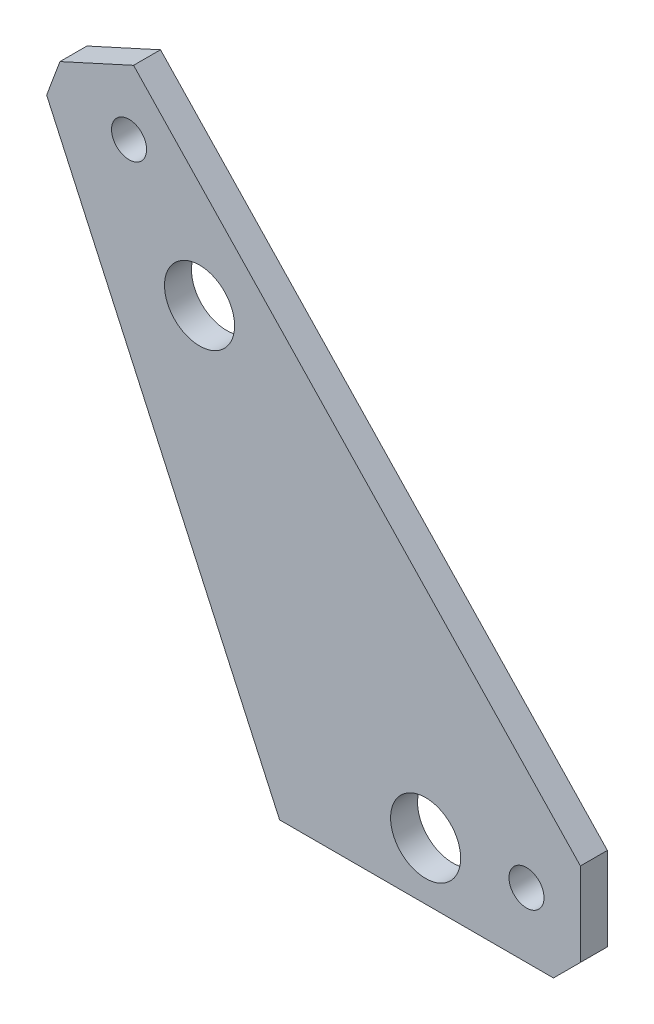
SolidWorks part; units mm, degrees
material "ASTM A36 Steel"
ref_plane "Front Plane" through (0, 0, 0) normal (0, 0, 1) x (1, 0, 0)
ref_plane "Top Plane" through (0, 0, 0) normal (0, 1, 0) x (1, 0, 0)
ref_plane "Right Plane" through (0, 0, 0) normal (1, 0, 0) x (0, 0, -1)
sketch "Sketch1" plane through (0, 0, 0) normal (0, 0, 1) x (1, 0, 0)
  line L0 (103.4222, -51.9957) -> (103.4222, -82.9957)
  line L1 (93.4222, -92.9957) -> (-8.0533, -92.9957)
  line L2 (-8.2353, -92.8786) -> (-94.6153, 96.6649)
  line L3 (-89.6626, 109.9114) -> (-62.3638, 122.3522)
  line L4 (103.4222, -51.9957) -> (-62.3638, 122.3522)
  line L5 (103.4222, -82.9957) -> (93.4222, -92.9957)
  line L6 (-94.6153, 96.6649) -> (-89.6626, 109.9114)
  arc A0 (-8.2353, -92.8786) -> (-8.0533, -92.9957) centre (-8.0533, -92.7957) ccw
extrude "Boss-Extrude1" add sketch "Sketch1" along normal blind 10
sketch "Sketch2" plane through (0, 0, 10) normal (0, 0, 1) x (1, 0, 0)
  line L0 (103.4222, -82.9957) -> (103.4222, -51.9957) construction
  line L1 (-8.0533, -92.9957) -> (93.4222, -92.9957) construction
  circle A0 centre (83.4222, -68.9957) radius 6.5
  circle A1 centre (-64.0311, 97.6811) radius 6.5
  circle A2 centre (-37.8884, 57.4249) radius 13
  circle A3 centre (45.986, -71.7304) radius 13
  dimension "D1" = 13
  dimension "D2" = 20
  dimension "D5" = 13
  dimension "D7" = 26
  dimension "D8" = 48
  dimension "D9" = 26
  dimension "D10" = 154
  dimension "D3" = 24
extrude "Cut-Extrude1" cut sketch "Sketch2" against normal blind 10
